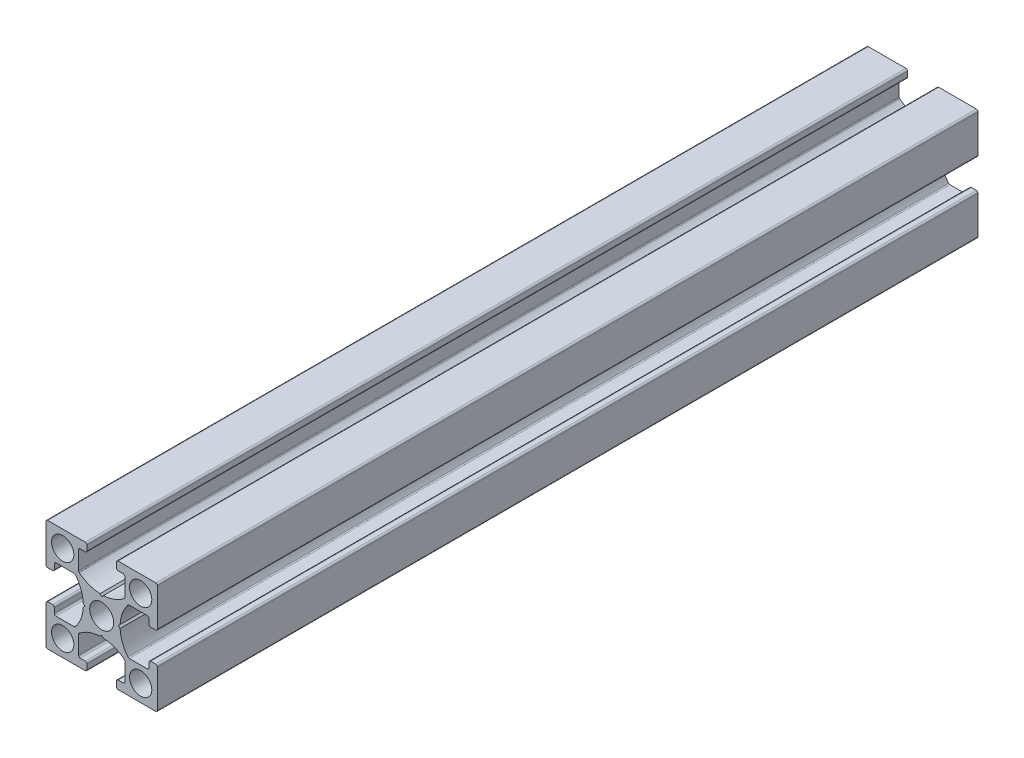
SolidWorks part; units mm, degrees
ref_plane "정면" through (0, 0, 0) normal (0, 0, 1) x (1, 0, 0)
ref_plane "윗면" through (0, 0, 0) normal (0, 1, 0) x (1, 0, 0)
ref_plane "우측면" through (0, 0, 0) normal (1, 0, 0) x (0, 0, -1)
sketch "Model" plane through (0, 0, 0) normal (0, 0, 1) x (1, 0, 0)
  line L0 (2307.7639, 1192.1343) -> (2307.7639, 1195.3915)
  line L1 (2307.4639, 1195.6915) -> (2306.5639, 1195.6915)
  line L2 (2306.2639, 1195.9915) -> (2306.2639, 1196.8915)
  line L3 (2306.5639, 1197.1915) -> (2313.3139, 1197.1915)
  line L4 (2313.6139, 1196.8915) -> (2313.6139, 1190.1415)
  line L5 (2313.3139, 1189.8415) -> (2312.4139, 1189.8415)
  line L6 (2312.1139, 1190.1415) -> (2312.1139, 1191.0415)
  line L7 (2311.8139, 1191.3415) -> (2308.5567, 1191.3415)
  line L8 (2306.9212, 1187.4988) -> (2306.6139, 1187.1915)
  line L9 (2306.6139, 1187.1915) -> (2306.9212, 1186.8843)
  line L10 (2308.5567, 1183.0415) -> (2311.8139, 1183.0415)
  line L11 (2312.1139, 1183.3415) -> (2312.1139, 1184.2415)
  line L12 (2312.4139, 1184.5415) -> (2313.3139, 1184.5415)
  line L13 (2313.6139, 1184.2415) -> (2313.6139, 1177.4915)
  line L14 (2313.3139, 1177.1915) -> (2306.5639, 1177.1915)
  line L15 (2306.2639, 1177.4915) -> (2306.2639, 1178.3915)
  line L16 (2306.5639, 1178.6915) -> (2307.4639, 1178.6915)
  line L17 (2307.7639, 1178.9915) -> (2307.7639, 1182.2488)
  line L18 (2303.9212, 1183.8843) -> (2303.6139, 1184.1915)
  line L19 (2303.6139, 1184.1915) -> (2303.3066, 1183.8843)
  line L20 (2299.4639, 1182.2488) -> (2299.4639, 1178.9915)
  line L21 (2299.7639, 1178.6915) -> (2300.6639, 1178.6915)
  line L22 (2300.9639, 1178.3915) -> (2300.9639, 1177.4915)
  line L23 (2300.6639, 1177.1915) -> (2293.9139, 1177.1915)
  line L24 (2293.6139, 1177.4915) -> (2293.6139, 1184.2415)
  line L25 (2293.9139, 1184.5415) -> (2294.8139, 1184.5415)
  line L26 (2295.1139, 1184.2415) -> (2295.1139, 1183.3415)
  line L27 (2295.4139, 1183.0415) -> (2298.6712, 1183.0415)
  line L28 (2300.3066, 1186.8843) -> (2300.6139, 1187.1915)
  line L29 (2300.6139, 1187.1915) -> (2300.3066, 1187.4988)
  line L30 (2298.6712, 1191.3415) -> (2295.4139, 1191.3415)
  line L31 (2295.1139, 1191.0415) -> (2295.1139, 1190.1415)
  line L32 (2294.8139, 1189.8415) -> (2293.9139, 1189.8415)
  line L33 (2293.6139, 1190.1415) -> (2293.6139, 1196.8915)
  line L34 (2293.9139, 1197.1915) -> (2300.6639, 1197.1915)
  line L35 (2300.9639, 1196.8915) -> (2300.9639, 1195.9915)
  line L36 (2300.6639, 1195.6915) -> (2299.7639, 1195.6915)
  line L37 (2299.4639, 1195.3915) -> (2299.4639, 1192.1343)
  line L38 (2303.3066, 1190.4988) -> (2303.6139, 1190.1915)
  line L39 (2303.6139, 1190.1915) -> (2303.9212, 1190.4988)
  circle A0 centre (2303.6139, 1187.1915) radius 2.15
  circle A1 centre (2296.6139, 1194.1915) radius 2
  circle A2 centre (2296.6139, 1180.1915) radius 2
  circle A3 centre (2310.6139, 1194.1915) radius 2
  circle A4 centre (2310.6139, 1180.1915) radius 2
  arc A5 (2307.7639, 1195.3915) -> (2307.4639, 1195.6915) centre (2307.4639, 1195.3915) ccw
  arc A6 (2306.2639, 1195.9915) -> (2306.5639, 1195.6915) centre (2306.5639, 1195.9915) ccw
  arc A7 (2306.5639, 1197.1915) -> (2306.2639, 1196.8915) centre (2306.5639, 1196.8915) ccw
  arc A8 (2313.6139, 1196.8915) -> (2313.3139, 1197.1915) centre (2313.3139, 1196.8915) ccw
  arc A9 (2313.3139, 1189.8415) -> (2313.6139, 1190.1415) centre (2313.3139, 1190.1415) ccw
  arc A10 (2312.1139, 1190.1415) -> (2312.4139, 1189.8415) centre (2312.4139, 1190.1415) ccw
  arc A11 (2312.1139, 1191.0415) -> (2311.8139, 1191.3415) centre (2311.8139, 1191.0415) ccw
  arc A12 (2308.5567, 1191.3415) -> (2308.3217, 1191.2281) centre (2308.5567, 1191.0415) ccw
  arc A13 (2308.3217, 1191.2281) -> (2306.9212, 1187.4988) centre (2313.4048, 1187.1915) ccw
  arc A14 (2306.9212, 1186.8843) -> (2308.3217, 1183.155) centre (2313.4048, 1187.1915) ccw
  arc A15 (2308.3217, 1183.155) -> (2308.5567, 1183.0415) centre (2308.5567, 1183.3415) ccw
  arc A16 (2311.8139, 1183.0415) -> (2312.1139, 1183.3415) centre (2311.8139, 1183.3415) ccw
  arc A17 (2312.4139, 1184.5415) -> (2312.1139, 1184.2415) centre (2312.4139, 1184.2415) ccw
  arc A18 (2313.6139, 1184.2415) -> (2313.3139, 1184.5415) centre (2313.3139, 1184.2415) ccw
  arc A19 (2313.3139, 1177.1915) -> (2313.6139, 1177.4915) centre (2313.3139, 1177.4915) ccw
  arc A20 (2306.2639, 1177.4915) -> (2306.5639, 1177.1915) centre (2306.5639, 1177.4915) ccw
  arc A21 (2306.5639, 1178.6915) -> (2306.2639, 1178.3915) centre (2306.5639, 1178.3915) ccw
  arc A22 (2307.4639, 1178.6915) -> (2307.7639, 1178.9915) centre (2307.4639, 1178.9915) ccw
  arc A23 (2307.7639, 1182.2488) -> (2307.6505, 1182.4837) centre (2307.4639, 1182.2488) ccw
  arc A24 (2307.6505, 1182.4837) -> (2303.9212, 1183.8843) centre (2303.6139, 1177.4007) ccw
  arc A25 (2303.3066, 1183.8843) -> (2299.5774, 1182.4837) centre (2303.6139, 1177.4007) ccw
  arc A26 (2299.5774, 1182.4837) -> (2299.4639, 1182.2488) centre (2299.7639, 1182.2488) ccw
  arc A27 (2299.4639, 1178.9915) -> (2299.7639, 1178.6915) centre (2299.7639, 1178.9915) ccw
  arc A28 (2300.9639, 1178.3915) -> (2300.6639, 1178.6915) centre (2300.6639, 1178.3915) ccw
  arc A29 (2300.6639, 1177.1915) -> (2300.9639, 1177.4915) centre (2300.6639, 1177.4915) ccw
  arc A30 (2293.6139, 1177.4915) -> (2293.9139, 1177.1915) centre (2293.9139, 1177.4915) ccw
  arc A31 (2293.9139, 1184.5415) -> (2293.6139, 1184.2415) centre (2293.9139, 1184.2415) ccw
  arc A32 (2295.1139, 1184.2415) -> (2294.8139, 1184.5415) centre (2294.8139, 1184.2415) ccw
  arc A33 (2295.1139, 1183.3415) -> (2295.4139, 1183.0415) centre (2295.4139, 1183.3415) ccw
  arc A34 (2298.6712, 1183.0415) -> (2298.9061, 1183.155) centre (2298.6712, 1183.3415) ccw
  arc A35 (2298.9061, 1183.155) -> (2300.3066, 1186.8843) centre (2293.8231, 1187.1915) ccw
  arc A36 (2300.3066, 1187.4988) -> (2298.9061, 1191.2281) centre (2293.8231, 1187.1915) ccw
  arc A37 (2298.9061, 1191.2281) -> (2298.6712, 1191.3415) centre (2298.6712, 1191.0415) ccw
  arc A38 (2295.4139, 1191.3415) -> (2295.1139, 1191.0415) centre (2295.4139, 1191.0415) ccw
  arc A39 (2294.8139, 1189.8415) -> (2295.1139, 1190.1415) centre (2294.8139, 1190.1415) ccw
  arc A40 (2293.6139, 1190.1415) -> (2293.9139, 1189.8415) centre (2293.9139, 1190.1415) ccw
  arc A41 (2293.9139, 1197.1915) -> (2293.6139, 1196.8915) centre (2293.9139, 1196.8915) ccw
  arc A42 (2300.9639, 1196.8915) -> (2300.6639, 1197.1915) centre (2300.6639, 1196.8915) ccw
  arc A43 (2300.6639, 1195.6915) -> (2300.9639, 1195.9915) centre (2300.6639, 1195.9915) ccw
  arc A44 (2299.7639, 1195.6915) -> (2299.4639, 1195.3915) centre (2299.7639, 1195.3915) ccw
  arc A45 (2299.4639, 1192.1343) -> (2299.5774, 1191.8994) centre (2299.7639, 1192.1343) ccw
  arc A46 (2299.5774, 1191.8994) -> (2303.3066, 1190.4988) centre (2303.6139, 1196.9824) ccw
  arc A47 (2303.9212, 1190.4988) -> (2307.6505, 1191.8994) centre (2303.6139, 1196.9824) ccw
  arc A48 (2307.6505, 1191.8994) -> (2307.7639, 1192.1343) centre (2307.4639, 1192.1343) ccw
extrude "보스-돌출1" add sketch "Model" along normal blind 147.38
sketch "스케치1" plane through (0, 1197.1915, 0) normal (0, 1, 0) x (1, 0, 0)
  line L0 (2303.6139, -147.38) -> (2303.6139, 0) construction
  line L2 (2307.6505, 0) -> (2303.9212, 0) construction
  line L3 (2303.9212, -147.38) -> (2307.6505, -147.38) construction
  circle A0 centre (2303.6139, -30) radius 2.5
  circle A1 centre (2303.6139, -117.38) radius 2.5
  circle A2 centre (2303.6139, -73.69) radius 2.5
  dimension "D1" = 30
  dimension "D2" = 30
extrude "컷-돌출1" cut sketch "스케치1" against normal through all
